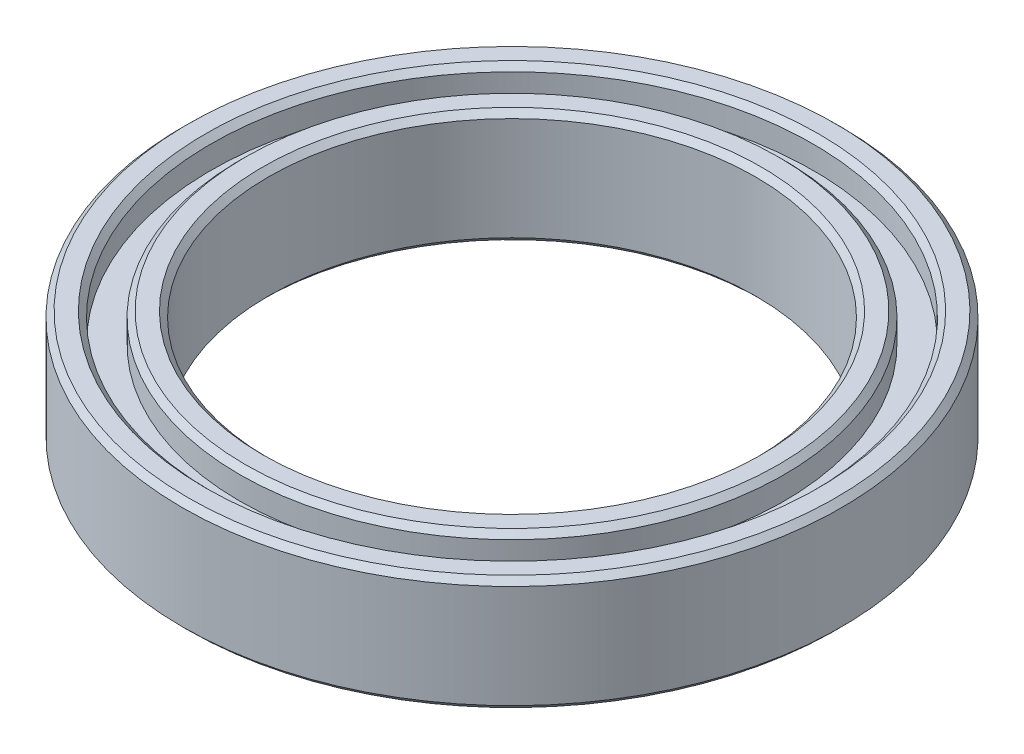
SolidWorks part; units mm, degrees
ref_plane "Front Plane" through (0, 0, 0) normal (0, 0, 1) x (1, 0, 0)
ref_plane "Top Plane" through (0, 0, 0) normal (0, 1, 0) x (1, 0, 0)
ref_plane "Right Plane" through (0, 0, 0) normal (1, 0, 0) x (0, 0, -1)
sketch "Sketch1" plane through (0, 0, 0) normal (0, 1, 0) x (1, 0, 0)
  circle A0 centre (0, 0) radius 11.5
  circle A1 centre (0, 0) radius 8.5
  dimension "D1" = 23
  dimension "D2" = 17
extrude "Boss-Extrude1" add sketch "Sketch1" along normal blind 4
sketch "Sketch2" plane through (0, 4, 0) normal (0, 1, 0) x (1, 0, 0)
  circle A0 centre (0, 0) radius 9.5
  circle A1 centre (0, 0) radius 10.5
  dimension "D1" = 21
  dimension "D2" = 19
extrude "Cut-Extrude1" cut sketch "Sketch2" against normal blind 1
sketch "Sketch3" plane through (0, 0, 0) normal (0, -1, 0) x (1, 0, 0)
  circle A0 centre (0, 0) radius 9.5
  circle A1 centre (0, 0) radius 10.5
  dimension "D1" = 21
  dimension "D2" = 19
extrude "Cut-Extrude2" cut sketch "Sketch3" against normal blind 1
chamfer "Chamfer1" distance 0.2 angle 45 8 edges at (0, 4, 9.5) (0, 4, 8.5) (0, 4, 11.5) (0, 4, 10.5) (0, 0, 11.5) (0, 0, -10.5) (0, 0, -9.5) (0, 0, 8.5)
